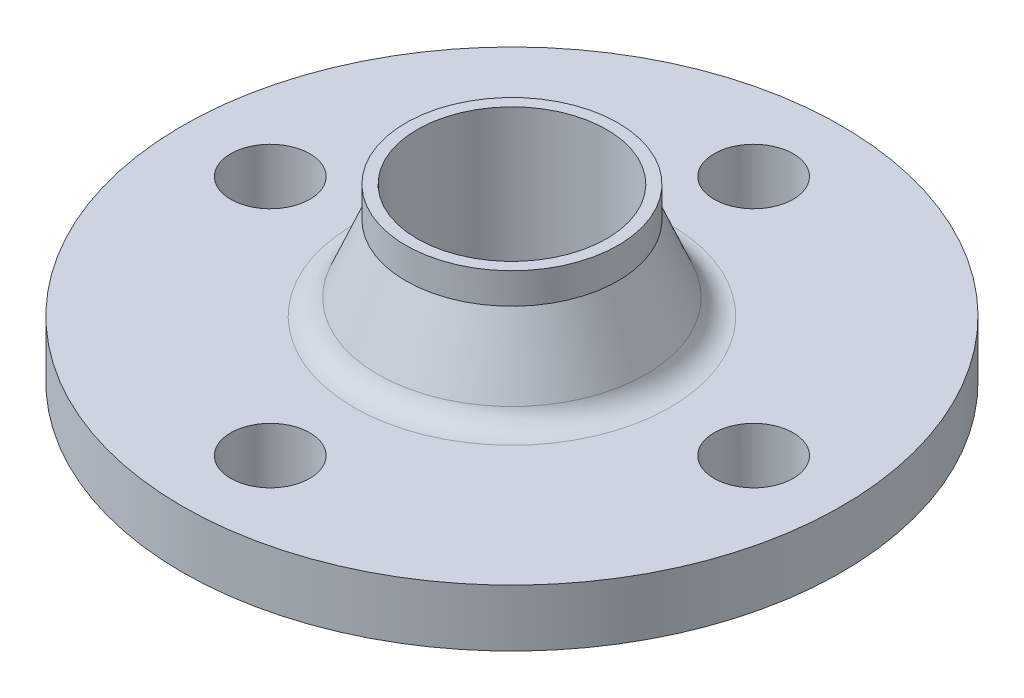
SolidWorks part; units mm, degrees
ref_plane "Płaszczyzna przednia" through (0, 0, 0) normal (0, 0, 1) x (1, 0, 0)
ref_plane "Płaszczyzna górna" through (0, 0, 0) normal (0, 1, 0) x (1, 0, 0)
ref_plane "Płaszczyzna prawa" through (0, 0, 0) normal (1, 0, 0) x (0, 0, -1)
ref_plane "Płaszczyzna1" through (0, 0, 0) normal (0, 0, -1) x (-1, 0, 0)
sketch "Szkic1" plane through (0, 0, 0) normal (0, 0, -1) x (-1, 0, 0)
  line L0 (-75, 3) -> (0, 3)
  line L1 (0, 3) -> (0, 16)
  line L2 (0, 16) -> (-75, 16)
  line L3 (-75, 16) -> (-75, 3)
  line L4 (0, 3) -> (0, 16) construction
revolve "Obrót1" add sketch "Szkic1" angle 360 about L4
sketch "Szkic2" plane through (0, 16, 0) normal (0, 1, 0) x (-1, 0, 0)
  circle A0 centre (0, 0) radius 32
extrude "Dodanie-wyciągnięcie1" add sketch "Szkic2" along normal blind 19 draft 22.448
sketch "Szkic3" plane through (0, 35, 0) normal (0, 1, 0) x (-1, 0, 0)
  circle A0 centre (0, 0) radius 24.15
extrude "Dodanie-wyciągnięcie2" add sketch "Szkic3" along normal blind 7
sketch "Szkic4" plane through (0, 3, 0) normal (0, -1, 0) x (1, 0, 0)
  circle A0 centre (0, 0) radius 47
extrude "Dodanie-wyciągnięcie3" add sketch "Szkic4" along normal blind 3 draft 45
hole_wizard "Otwór Ø18.0 (18)1" positions "Szkic6" profile "Szkic5" hole size "Ø18.0" standard "Ansi Metric"
sketch "Szkic6" plane through (0, 16, 0) normal (0, 1, 0) x (1, 0, 0)
  point P0 (-55, 0)
  point P1 (55, 0)
  point P2 (0, -55)
  point P3 (0, 55)
sketch "Szkic5" plane through (-55, 16, 0) normal (1, 0, 0) x (0, 0, 1)
  line L0 (0, 0) -> (0, 13)
  line L1 (0, 13) -> (9, 13)
  line L2 (9, 13) -> (9, 0)
  line L5 (9, 0) -> (0, 0)
  line L10 (0, 13) -> (-9, 13) construction
  line L11 (0, -6.35) -> (0, 107.95) construction
  dimension "Średnica otworu" = 18
  dimension "Głębokość otworu" = 13
  dimension "Kąt wiertła" = 180
hole_wizard "Otwór pod śrubę M391" positions "Szkic8" profile "Szkic7" hole size "M39" standard "Ansi Metric"
sketch "Szkic8" plane through (0, 42, 0) normal (0, 1, 0) x (1, 0, 0)
  point P0 (0, 0)
sketch "Szkic7" plane through (0, 42, 0) normal (1, 0, 0) x (0, 0, 1)
  line L0 (0, 0) -> (0, 42)
  line L1 (0, 42) -> (21.55, 42)
  line L2 (21.55, 42) -> (21.55, 0)
  line L5 (21.55, 0) -> (0, 0)
  line L11 (0, -6.35) -> (0, 107.95) construction
  dimension "Średnica otworu na wylot" = 43.1
  dimension "Głębokość otworu na wylot" = 42
fillet "Zaokrąglenie1" radius 6 1 edges at (0, 16, 32)
